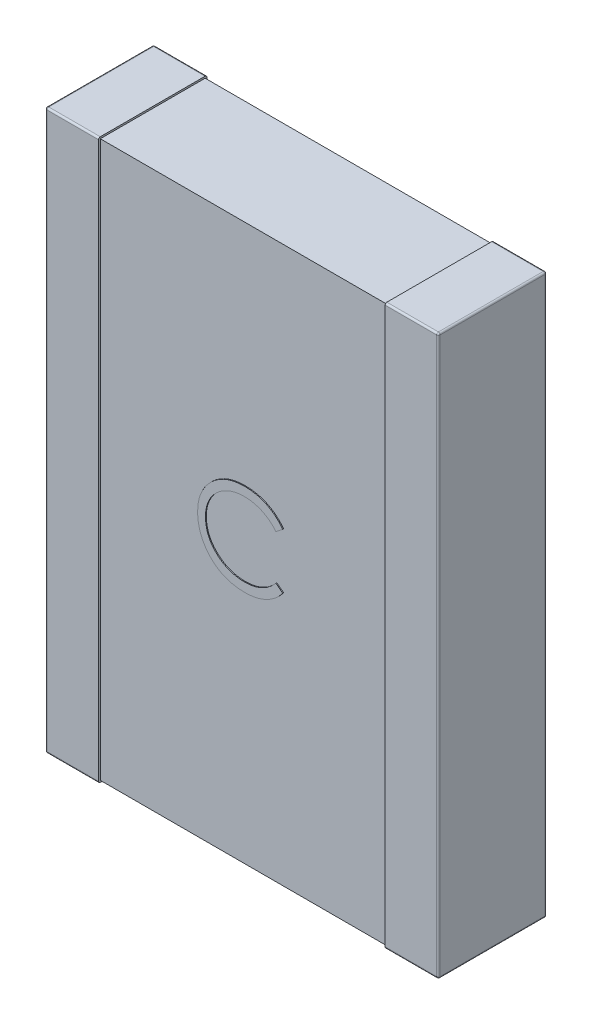
SolidWorks part; units mm, degrees
ref_plane "前视基准面" through (0, 0, 0) normal (0, 0, 1) x (1, 0, 0)
ref_plane "上视基准面" through (0, 0, 0) normal (0, 1, 0) x (1, 0, 0)
ref_plane "右视基准面" through (0, 0, 0) normal (1, 0, 0) x (0, 0, -1)
sketch "草图3" plane through (0, 0, 0) normal (0, 0, 1) x (1, 0, 0)
  line L0 (0, 4.2576) -> (0, -4.4067) construction
  line L1 (-2.25, 3.2) -> (-1.64, 3.2)
  line L2 (-2.25, 3.2) -> (-2.25, -3.2)
  line L3 (-2.25, -3.2) -> (-1.64, -3.2)
  line L4 (-1.64, 3.2) -> (-1.64, -3.2)
  line L5 (-2.25, 3.2) -> (-1.64, -3.2) construction
  line L6 (-2.25, -3.2) -> (-1.64, 3.2) construction
  line L7 (2.25, -3.2) -> (1.64, 3.2) construction
  line L8 (2.25, 3.2) -> (1.64, -3.2) construction
  line L9 (1.64, 3.2) -> (1.64, -3.2)
  line L10 (2.25, -3.2) -> (1.64, -3.2)
  line L11 (2.25, 3.2) -> (2.25, -3.2)
  line L12 (2.25, 3.2) -> (1.64, 3.2)
  point P0 (-1.945, 0)
  point P12 (1.945, 0)
  dimension "D1" = 0.61
  dimension "D2" = 6.4
  dimension "D3" = 2.25
extrude "凸台-拉伸1" add sketch "草图3" along normal blind 1.22 and the other way blind 0.02
sketch "草图5" plane through (0, 0, 0) normal (1, 0, 0) x (0, 0, -1)
  line L0 (0, 3.18) -> (0, -3.18)
  line L1 (0, -3.18) -> (-1.2, -3.18)
  line L2 (-1.2, -3.18) -> (-1.2, 3.18)
  line L3 (-1.2, 3.18) -> (0, 3.18)
  dimension "D1" = 6.36
  dimension "D2" = 1.2
extrude "凸台-拉伸3" add sketch "草图5" along normal mid plane 3.32
fillet "圆角3" radius 0.02 16 edges at (2.25, 0, -0.02) (2.25, -3.2, 0.6) (2.25, 0, 1.22) (2.25, 3.2, 0.6) (-2.25, 0, -0.02) (-2.25, 3.2, 0.6) (-2.25, 0, 1.22) (-2.25, -3.2, 0.6) (1.945, 3.2, -0.02) (1.945, -3.2, -0.02) (1.945, -3.2, 1.22) (1.945, 3.2, 1.22) (-1.945, -3.2, -0.02) (-1.945, -3.2, 1.22) (-1.945, 3.2, -0.02) (-1.945, 3.2, 1.22)
sketch "草图6" plane through (0, 0, 1.2) normal (0, 0, 1) x (1, 0, 0)
  text T0 "C" font "Century Gothic" height 1
extrude "凸台-拉伸4" add sketch "草图6" along normal blind 0.01
